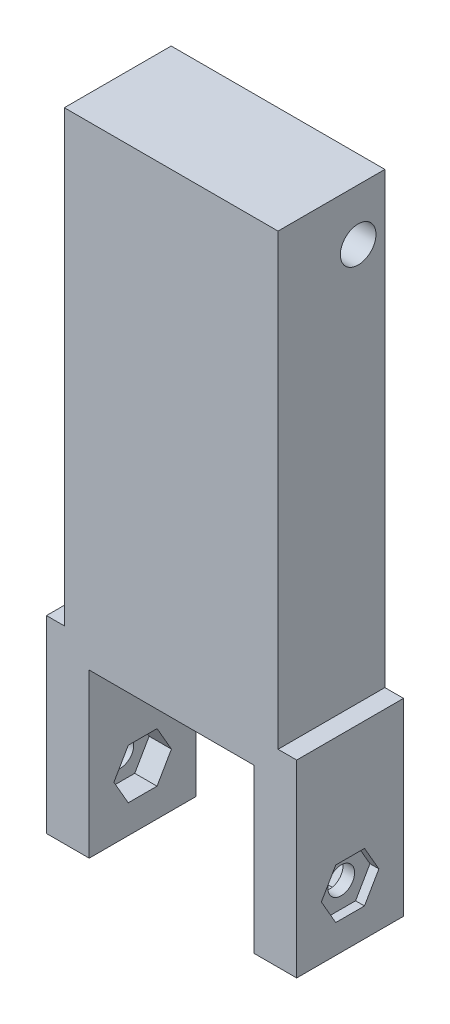
SolidWorks part; units mm, degrees
ref_plane "정면" through (0, 0, 0) normal (0, 0, 1) x (1, 0, 0)
ref_plane "윗면" through (0, 0, 0) normal (0, 1, 0) x (1, 0, 0)
ref_plane "우측면" through (0, 0, 0) normal (1, 0, 0) x (0, 0, -1)
sketch "스케치1" plane through (0, 0, 0) normal (0, 0, 1) x (1, 0, 0)
  line L0 (-11.9944, 44.775) -> (-11.9944, -5.625)
  line L1 (-11.9944, 44.775) -> (12.0056, 44.775)
  line L2 (12.0056, 44.775) -> (12.0056, -5.6271)
  line L3 (9.3002, -26.8271) -> (14.1002, -26.8271)
  line L4 (14.1002, -5.6271) -> (12.0056, -5.6271)
  line L5 (-11.9944, -5.625) -> (-13.9998, -5.625)
  line L9 (0.0056, 44.775) -> (0.0056, -20.9932) construction
  line L10 (9.3002, -8.5271) -> (-9.1998, -8.525)
  line L12 (9.3002, -26.8271) -> (9.3002, -8.5271)
  line L14 (14.1002, -26.8271) -> (14.1002, -5.6271)
  line L15 (-9.1998, -26.825) -> (-13.9998, -26.825)
  line L16 (-9.1998, -26.825) -> (-9.1998, -8.525)
  line L18 (-13.9998, -26.825) -> (-13.9998, -5.625)
  dimension "D2" = 12
  dimension "D4" = 21.2
  dimension "D3" = 21.2
  dimension "D1" = 50.4
  dimension "D5" = 18.3
  dimension "D6" = 18.3
  dimension "D7" = 18.5
  dimension "D8" = 4.8
  dimension "D9" = 4.8
extrude "보스-돌출1" add sketch "스케치1" along normal blind 12
ref_plane "평면11" through (12.0056, 0, 0) normal (1, 0, 0) x (0, 0, -1)
ref_plane "평면12" through (12.0056, 0, 0) normal (1, 0, 0) x (0, 0, -1)
ref_plane "평면13" through (0.0056, 0, 0) normal (1, 0, 0) x (0, 0, -1)
ref_plane "평면14" through (14.1002, 0, 0) normal (1, 0, 0) x (0, 0, -1)
sketch "스케치20" plane through (14.1002, 0, 0) normal (1, 0, 0) x (0, 0, -1)
  line L0 (-4.385, -23.6262) -> (-7.615, -23.6262)
  line L1 (-7.615, -23.6262) -> (-9.2284, -20.8243)
  line L2 (-9.2284, -20.8243) -> (-7.6134, -18.0307)
  line L3 (-7.6134, -18.0307) -> (-4.3803, -18.0307)
  line L4 (-4.3803, -18.0307) -> (-2.7684, -20.8298)
  line L5 (-2.7684, -20.8298) -> (-4.385, -23.6262)
  line L6 (-7.615, -23.6262) -> (-4.3803, -18.0307) construction
  line L7 (-7.6134, -18.0307) -> (-4.385, -23.6262) construction
  line L8 (-2.7684, -20.8298) -> (-9.2284, -20.8243) construction
  line L11 (-12, -26.8271) -> (0, -26.8271) construction
  line L13 (0, -26.8271) -> (0, -5.6271) construction
  point P0 (-6, -20.8271)
  dimension "D1" = 3.2332
  dimension "D2" = 3.2332
  dimension "D3" = 3.23
  dimension "D4" = 3.23
  dimension "D5" = 3.2268
  dimension "D6" = 3.23
  dimension "D7" = 6
  dimension "D8" = 6
extrude "컷-돌출12" cut sketch "스케치20" against normal blind 1
ref_plane "평면15" through (-13.9998, 0, 0) normal (-1, 0, 0) x (0, 0, 1)
sketch "스케치21" plane through (-13.9998, 0, 0) normal (-1, 0, 0) x (0, 0, 1)
  line L0 (7.6118, -23.6241) -> (4.3818, -23.6241)
  line L1 (4.3818, -23.6241) -> (2.7684, -20.8223)
  line L2 (2.7684, -20.8223) -> (4.3834, -18.0287)
  line L3 (4.3834, -18.0287) -> (7.6166, -18.0287)
  line L4 (7.6166, -18.0287) -> (9.2284, -20.8278)
  line L5 (9.2284, -20.8278) -> (7.6118, -23.6241)
  line L6 (4.3818, -23.6241) -> (7.6166, -18.0287) construction
  line L7 (4.3834, -18.0287) -> (7.6118, -23.6241) construction
  line L8 (9.2284, -20.8278) -> (2.7684, -20.8223) construction
  line L9 (12, -5.625) -> (12, -26.825) construction
  line L10 (12, -26.825) -> (0, -26.825) construction
  point P0 (6, -20.825)
  dimension "D1" = 3.2332
  dimension "D2" = 3.2332
  dimension "D3" = 3.23
  dimension "D4" = 3.23
  dimension "D5" = 3.2268
  dimension "D6" = 3.23
  dimension "D7" = 6
  dimension "D8" = 6
extrude "컷-돌출13" cut sketch "스케치21" against normal blind 1
ref_plane "평면16" through (9.3002, 0, 0) normal (-1, 0, 0) x (0, 0, 1)
sketch "스케치22" plane through (9.3002, 0, 0) normal (-1, 0, 0) x (0, 0, 1)
  line L0 (7.615, -23.6241) -> (4.385, -23.6241)
  line L1 (4.385, -23.6241) -> (2.7716, -20.8223)
  line L2 (2.7716, -20.8223) -> (4.3866, -18.0287)
  line L3 (4.3866, -18.0287) -> (7.6197, -18.0287)
  line L4 (7.6197, -18.0287) -> (9.2316, -20.8278)
  line L5 (9.2316, -20.8278) -> (7.615, -23.6241)
  line L6 (4.385, -23.6241) -> (7.6197, -18.0287) construction
  line L7 (4.3866, -18.0287) -> (7.615, -23.6241) construction
  line L8 (9.2316, -20.8278) -> (2.7716, -20.8223) construction
  line L11 (12, -26.825) -> (0, -26.825) construction
  line L12 (12, -5.625) -> (12, -26.825) construction
  point P0 (6, -20.825)
  dimension "D1" = 3.2332
  dimension "D2" = 3.2332
  dimension "D3" = 3.23
  dimension "D4" = 3.23
  dimension "D5" = 3.2268
  dimension "D6" = 3.23
  dimension "D7" = 6
  dimension "D8" = 6
extrude "컷-돌출14" cut sketch "스케치22" against normal blind 2.5
ref_plane "평면17" through (-9.1998, 0, 0) normal (1, 0, 0) x (0, 0, -1)
sketch "스케치25" plane through (-9.1998, 0, 0) normal (1, 0, 0) x (0, 0, -1)
  line L0 (-4.385, -23.6262) -> (-7.615, -23.6262)
  line L1 (-7.615, -23.6262) -> (-9.2284, -20.8243)
  line L2 (-9.2284, -20.8243) -> (-7.6134, -18.0307)
  line L3 (-7.6134, -18.0307) -> (-4.3803, -18.0307)
  line L4 (-4.3803, -18.0307) -> (-2.7684, -20.8298)
  line L5 (-2.7684, -20.8298) -> (-4.385, -23.6262)
  line L6 (-7.615, -23.6262) -> (-4.3803, -18.0307) construction
  line L7 (-7.6134, -18.0307) -> (-4.385, -23.6262) construction
  line L8 (-2.7684, -20.8298) -> (-9.2284, -20.8243) construction
  line L9 (0, -26.8271) -> (0, -5.6271) construction
  line L12 (-12, -26.8271) -> (0, -26.8271) construction
  point P0 (-6, -20.8271)
  dimension "D1" = 3.2332
  dimension "D2" = 3.2332
  dimension "D3" = 3.23
  dimension "D4" = 3.23
  dimension "D5" = 3.2268
  dimension "D6" = 3.23
  dimension "D7" = 6
  dimension "D8" = 6
extrude "컷-돌출16" cut sketch "스케치25" against normal blind 2.5
ref_plane "평면18" through (-12.9998, 0, 0) normal (-1, 0, 0) x (0, 0, 1)
sketch "스케치26" plane through (-12.9998, 0, 0) normal (-1, 0, 0) x (0, 0, 1)
  line L0 (12, -26.825) -> (0, -26.825) construction
  line L1 (0, -5.625) -> (0, -26.825) construction
  circle A0 centre (6, -20.825) radius 1.5
  dimension "D3" = 3
  dimension "D1" = 6
  dimension "D2" = 6
extrude "컷-돌출17" cut sketch "스케치26" against normal through all
ref_plane "평면19" through (12.0056, 0, 0) normal (1, 0, 0) x (0, 0, -1)
sketch "스케치27" plane through (12.0056, 0, 0) normal (1, 0, 0) x (0, 0, -1)
  line L0 (-12, -5.6271) -> (-12, 44.775) construction
  line L1 (-12, -26.8271) -> (0, -26.8271) construction
  circle A0 centre (-3, 38.9729) radius 2
  dimension "D1" = 9
  dimension "D3" = 4
  dimension "D2" = 65.8
extrude "컷-돌출18" cut sketch "스케치27" against normal through all
